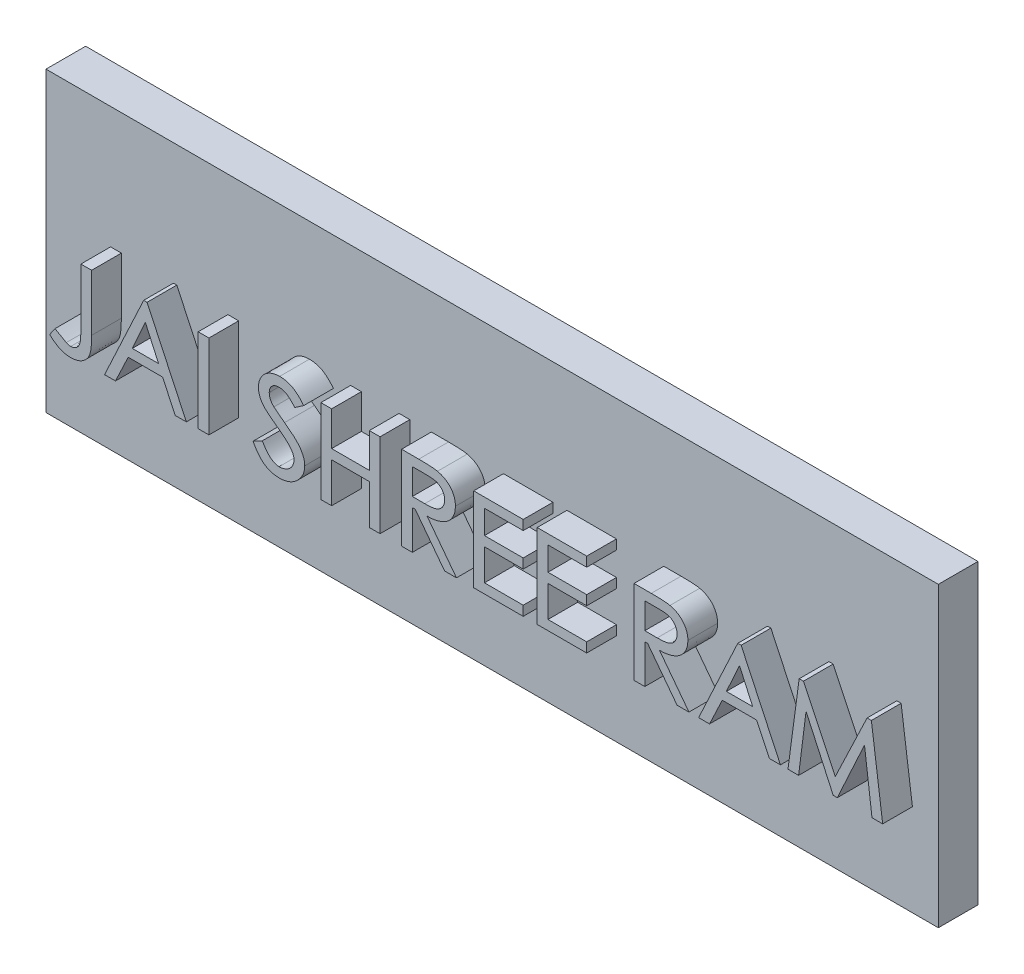
SolidWorks part; units mm, degrees
ref_plane "Front Plane" through (0, 0, 0) normal (0, 0, 1) x (1, 0, 0)
ref_plane "Top Plane" through (0, 0, 0) normal (0, 1, 0) x (1, 0, 0)
ref_plane "Right Plane" through (0, 0, 0) normal (1, 0, 0) x (0, 0, -1)
sketch "Sketch1" plane through (0, 0, 0) normal (0, 0, 1) x (1, 0, 0)
  line L1 (0, 0) -> (45, 0)
  line L2 (0, 0) -> (0, 15)
  line L3 (0, 15) -> (45, 15)
  line L4 (45, 0) -> (45, 15)
  dimension "D1" = 15
  dimension "D2" = 45
extrude "Boss-Extrude1" add sketch "Sketch1" along normal blind 2
sketch "Sketch2" plane through (0, 0, 2) normal (0, 0, 1) x (1, 0, 0)
  text T0 "JAI SHREE RAM" font "Century Gothic" height in points 16
extrude "Boss-Extrude2" add sketch "Sketch2" along normal blind 1.5
